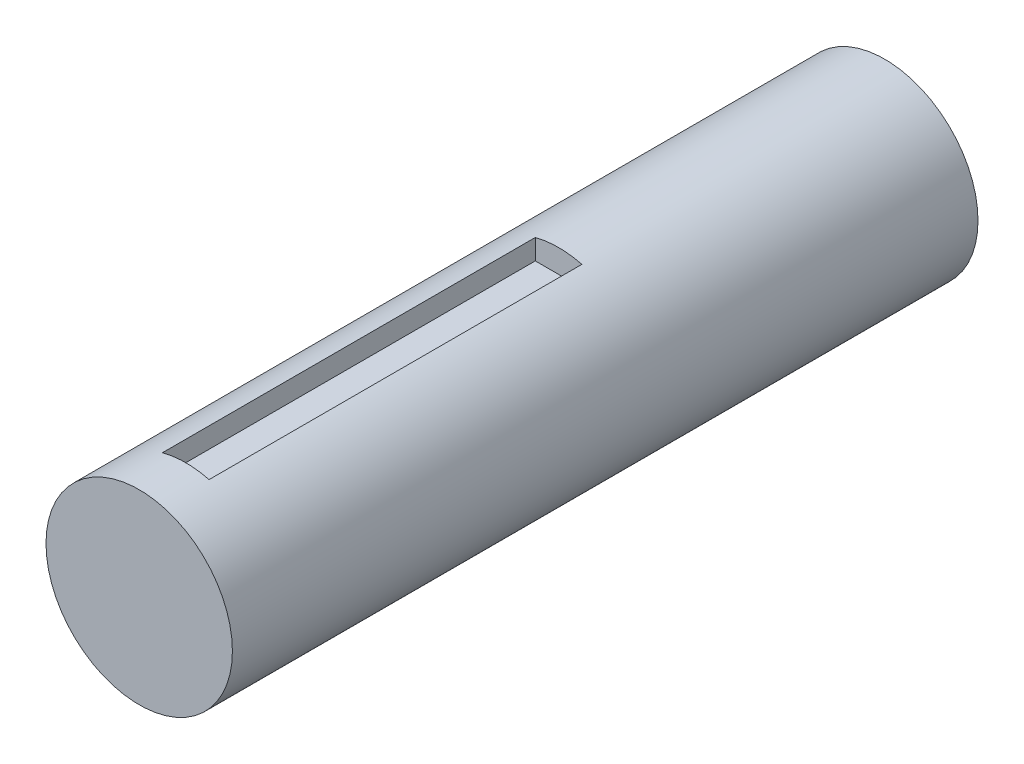
SolidWorks part; units mm, degrees
ref_plane "Front Plane" through (0, 0, 0) normal (0, 0, 1) x (1, 0, 0)
ref_plane "Top Plane" through (0, 0, 0) normal (0, 1, 0) x (1, 0, 0)
ref_plane "Right Plane" through (0, 0, 0) normal (1, 0, 0) x (0, 0, -1)
sketch "Sketch1" plane through (0, 0, 0) normal (0, 0, 1) x (1, 0, 0)
  circle A0 centre (0, 0) radius 10
  dimension "D1" = 20
extrude "Boss-Extrude1" add sketch "Sketch1" along normal blind 80
ref_plane "Plane1" through (0, 0, 75) normal (0, 0, -1) x (-1, 0, 0)
sketch "Sketch3" plane through (0, 0, 75) normal (0, 0, -1) x (-1, 0, 0)
  line L0 (0, 0) -> (0, 10) construction
  line L2 (-2.5, 7.5) -> (2.5, 7.5)
  line L3 (-2.5, 7.5) -> (-2.5, 12.5)
  line L4 (-2.5, 12.5) -> (2.5, 12.5)
  line L5 (2.5, 7.5) -> (2.5, 12.5)
  line L6 (-2.5, 7.5) -> (2.5, 12.5) construction
  line L7 (-2.5, 12.5) -> (2.5, 7.5) construction
  circle A0 centre (0, 0) radius 10 construction
  point P6 (0, 10)
  dimension "D1" = 5
  dimension "D2" = 2.5
  dimension "D3" = 5
extrude "Cut-Extrude1" cut sketch "Sketch3" along normal blind 40
ref_plane "Plane2" through (0, 0, 20) normal (0, 0, 1) x (1, 0, 0)
equation "\"D1@Cut-Extrude1\"=1.8*0.02"
